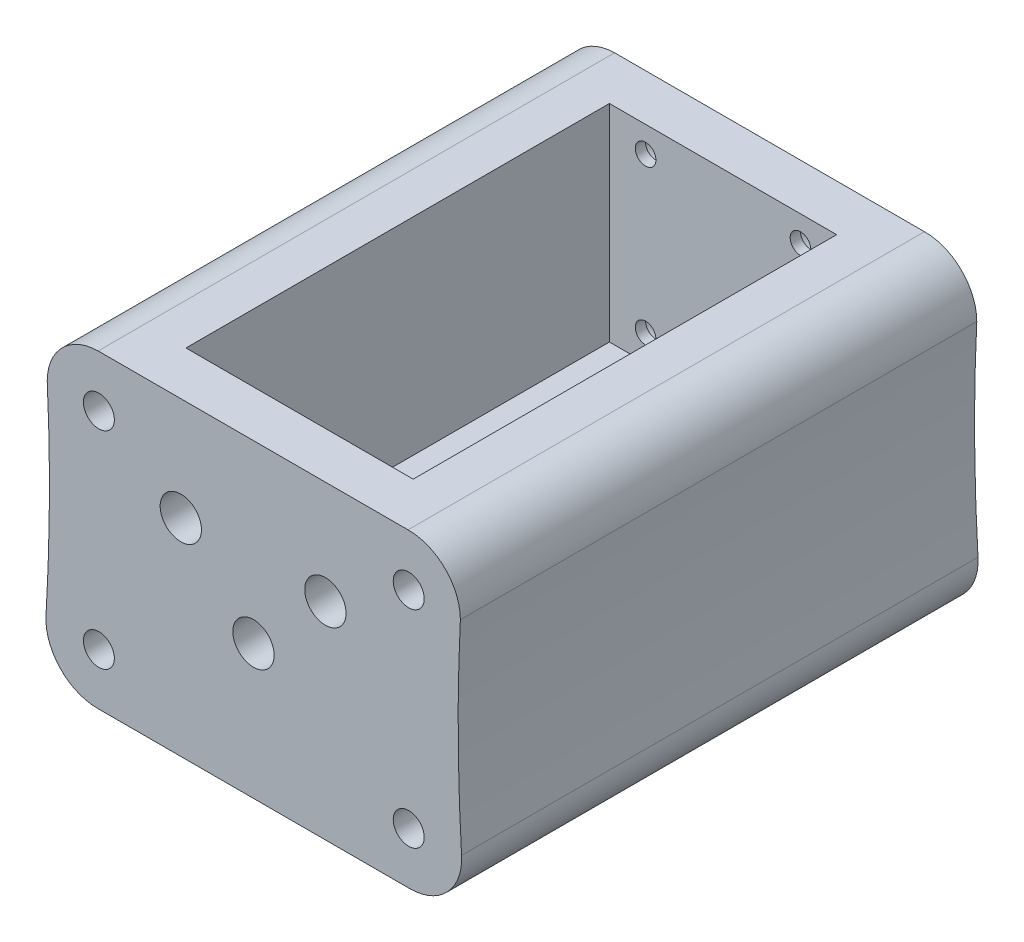
SolidWorks part; units mm, degrees
material "PET"
ref_plane "Front Plane" through (0, 0, 0) normal (0, 0, 1) x (1, 0, 0)
ref_plane "Top Plane" through (0, 0, 0) normal (0, 1, 0) x (1, 0, 0)
ref_plane "Right Plane" through (0, 0, 0) normal (1, 0, 0) x (0, 0, -1)
sketch "Sketch1" plane through (0, 0, 0) normal (0, 0, 1) x (1, 0, 0)
  line L18 (182.282, 145.9574) -> (161.0688, 167.1706)
  line L21 (130.7574, 145.5516) -> (160.7574, 115.5516)
  circle A30 centre (157.5808, 163.5882) radius 1.5
  arc A36 (154.0453, 167.1237) -> (161.0688, 167.1706) centre (157.5808, 163.5882) cw
  circle A44 centre (178.794, 142.375) radius 1.5
  arc A45 (182.3295, 138.8395) -> (182.282, 145.9574) centre (178.794, 142.375) ccw
  spline S1 degree 2 poles (130.7574, 145.5516) (143.6385, 155.6301) (154.0453, 167.1237) knots 0.858943 0.858943 0.858943 1 1 1
  spline S3 degree 2 poles (160.7574, 115.5516) (170.8359, 128.4327) (182.3295, 138.8395) knots 0.858943 0.858943 0.858943 1 1 1
  dimension "D7" = 3
  dimension "D4" = 5
  dimension "D5" = 30
  dimension "D6" = 30
  dimension "D23" = 5
extrude "Boss-Extrude2" add sketch "Sketch1" along normal blind 50
move or copy body "Body-Move/Copy1" bodies to move or copy 102 copy no rotation origin (157.2757, 142.0699, 0) rotation axis (0, 0, 1) rotation angle 45
ref_plane "Plane1" through (0, 144.1408, 0) normal (0, 1, 0) x (1, 0, 0)
sketch "Sketch2" plane through (0, 162.5009, 0) normal (0, 1, 0) x (1, 0, 0)
  line L3 (146.2089, -45.5) -> (168.2089, -45.5)
  line L4 (146.2089, -45.5) -> (146.2089, -4.5)
  line L5 (146.2089, -4.5) -> (168.2089, -4.5)
  line L6 (168.2089, -45.5) -> (168.2089, -4.5)
  line L7 (146.2089, -45.5) -> (168.2089, -4.5) construction
  line L8 (146.2089, -4.5) -> (168.2089, -45.5) construction
  point P8 (157.2089, -25)
  point P13 (157.2089, -25)
extrude "Cut-Extrude1" cut sketch "Sketch2" against normal blind 20
sketch "Sketch4" plane through (0, 0, 50) normal (0, 0, 1) x (1, 0, 0)
  line L0 (157.2089, 158.4186) -> (157.2089, 162.5009) construction
  line L2 (172.2089, 162.5009) -> (142.2089, 162.5009) construction
  line L3 (147.2089, 138.4186) -> (167.2089, 138.4186)
  line L4 (147.2089, 138.4186) -> (147.2089, 158.4186)
  line L5 (147.2089, 158.4186) -> (167.2089, 158.4186)
  line L6 (167.2089, 138.4186) -> (167.2089, 158.4186)
  line L7 (147.2089, 138.4186) -> (167.2089, 158.4186) construction
  line L8 (147.2089, 158.4186) -> (167.2089, 138.4186) construction
  line L9 (157.2458, 152.5009) -> (157.2458, 145.5) construction
  line L10 (157.2458, 152.5009) -> (164.2089, 152.5009) construction
  line L11 (157.2458, 152.5009) -> (150.2089, 152.5009) construction
  circle A7 centre (164.2089, 152.5009) radius 1
  circle A8 centre (150.2089, 152.5009) radius 1
  circle A9 centre (157.2458, 145.5) radius 1
extrude "Cut-Extrude6" cut sketch "Sketch4" against normal up to next contours A8 | A7 | A9
sketch "Sketch5" plane through (0, 0, 50) normal (0, 0, 1) x (1, 0, 0)
  circle A0 centre (150.2089, 152.5009) radius 2
  circle A1 centre (164.2089, 152.5009) radius 2
  circle A2 centre (157.2458, 145.5) radius 2
extrude "Cut-Extrude7" cut sketch "Sketch5" against normal blind 3.5
sketch "Sketch7" plane through (0, 0, 0) normal (0, 0, -1) x (-1, 0, 0)
  line L0 (-172.2089, 162.5009) -> (-142.2089, 162.5009) construction
  line L1 (-157.2089, 162.5009) -> (-147.2089, 162.5009) construction
  line L2 (-157.2089, 162.5009) -> (-167.2089, 162.5009) construction
  line L4 (-167.2089, 162.5009) -> (-147.2089, 162.5009)
  line L5 (-167.2089, 162.5009) -> (-167.2089, 142.5009)
  line L6 (-167.2089, 142.5009) -> (-147.2089, 142.5009)
  line L7 (-147.2089, 162.5009) -> (-147.2089, 142.5009)
  line L9 (-157.2089, 152.5009) -> (-149.7089, 160.0009) construction
  line L10 (-157.2089, 152.5009) -> (-164.7089, 160.0009) construction
  line L11 (-164.7089, 145.0009) -> (-157.2089, 152.5009) construction
  line L12 (-149.7089, 145.0009) -> (-157.2089, 152.5009) construction
  circle A0 centre (-149.7089, 160.0009) radius 1
  circle A1 centre (-164.7089, 160.0009) radius 1
  circle A2 centre (-149.7089, 145.0009) radius 1
  circle A3 centre (-164.7089, 145.0009) radius 1
  point P0 (-157.2089, 162.5009)
  point P8 (-157.2089, 152.5009)
  point P15 (-164.7089, 160.0009)
  point P16 (-149.7089, 160.0009)
  point P17 (-149.7089, 145.0009)
  point P18 (-164.7089, 145.0009)
extrude "Cut-Extrude11" cut sketch "Sketch7" against normal up to next contours A1 | A2 | A3 | A0
sketch "Sketch8" plane through (0, 0, 0) normal (0, 0, -1) x (-1, 0, 0)
  circle A0 centre (-164.7089, 160.0009) radius 2
  circle A1 centre (-149.7089, 160.0009) radius 2
  circle A2 centre (-149.7089, 145.0009) radius 2
  circle A3 centre (-164.7089, 145.0009) radius 2
extrude "Cut-Extrude12" cut sketch "Sketch8" against normal blind 3.5
sketch "Sketch9" plane through (0, 0, 0) normal (0, 0, -1) x (-1, 0, 0)
  line L0 (-172.2757, 157.5014) -> (-172.2757, 137.5014) construction
  line L1 (-142.2757, 157.5014) -> (-142.2757, 137.5014) construction
  circle A0 centre (-172.2757, 137.5014) radius 1.5
  circle A1 centre (-142.2757, 137.5014) radius 1.5
extrude "Cut-Extrude13" cut sketch "Sketch9" against normal through all
sketch "Sketch10" plane through (0, 0, 0) normal (0, 0, -1) x (-1, 0, 0)
  line L0 (-172.2757, 159.0014) -> (-172.2757, 162.5014) construction
  line L1 (-142.2757, 159.0014) -> (-142.2089, 162.5009) construction
  line L2 (-172.2757, 136.0014) -> (-172.2757, 132.5014) construction
  line L3 (-142.2757, 136.0014) -> (-142.2757, 132.5014) construction
  line L4 (-177.7835, 132.5014) -> (-136.7679, 132.5014)
  line L6 (-178.4889, 125.7806) -> (-136.0625, 125.7806)
  line L7 (-178.4889, 125.7806) -> (-178.4889, 132.5014)
  line L8 (-178.4889, 132.5014) -> (-136.0625, 132.5014)
  line L9 (-136.0625, 125.7806) -> (-136.0625, 132.5014)
  circle A0 centre (-172.2757, 157.5014) radius 1.5 construction
  arc A1 (-172.2089, 162.5009) -> (-177.2757, 157.5014) centre (-172.2757, 157.5014) ccw construction
  circle A2 centre (-142.2757, 157.5014) radius 1.5 construction
  circle A3 centre (-172.2757, 137.5014) radius 1.5 construction
  circle A4 centre (-142.2757, 137.5014) radius 1.5 construction
  parabola Q0 (-178.4889, 125.7806) -> (-177.2757, 157.5014) focus (-260.4465, 171.4962) apex (-182.818, 192.6364) construction
  parabola Q1 (-136.0625, 125.7806) -> (-137.2757, 157.5014) focus (-54.1049, 171.4962) apex (-131.7334, 192.6364) construction
  line M11 (-178.4889, 125.7806) -> (-136.0625, 125.7806)
  spline M12 degree 2 poles (-136.0625, 125.7806) (-138.0442, 142.0155) (-137.2757, 157.5014) knots 0.858943 0.858943 0.858943 1 1 1
  spline M16 degree 2 poles (-177.2757, 157.5014) (-176.5072, 142.0155) (-178.4889, 125.7806) knots 0.858943 0.858943 0.858943 1 1 1
extrude "Cut-Extrude14" cut sketch "Sketch10" against normal through all contours L4 M16 M11 M12
fillet "Fillet1" radius 5 2 edges at (136.7679, 132.5014, 25) (177.7835, 132.5014, 25)
